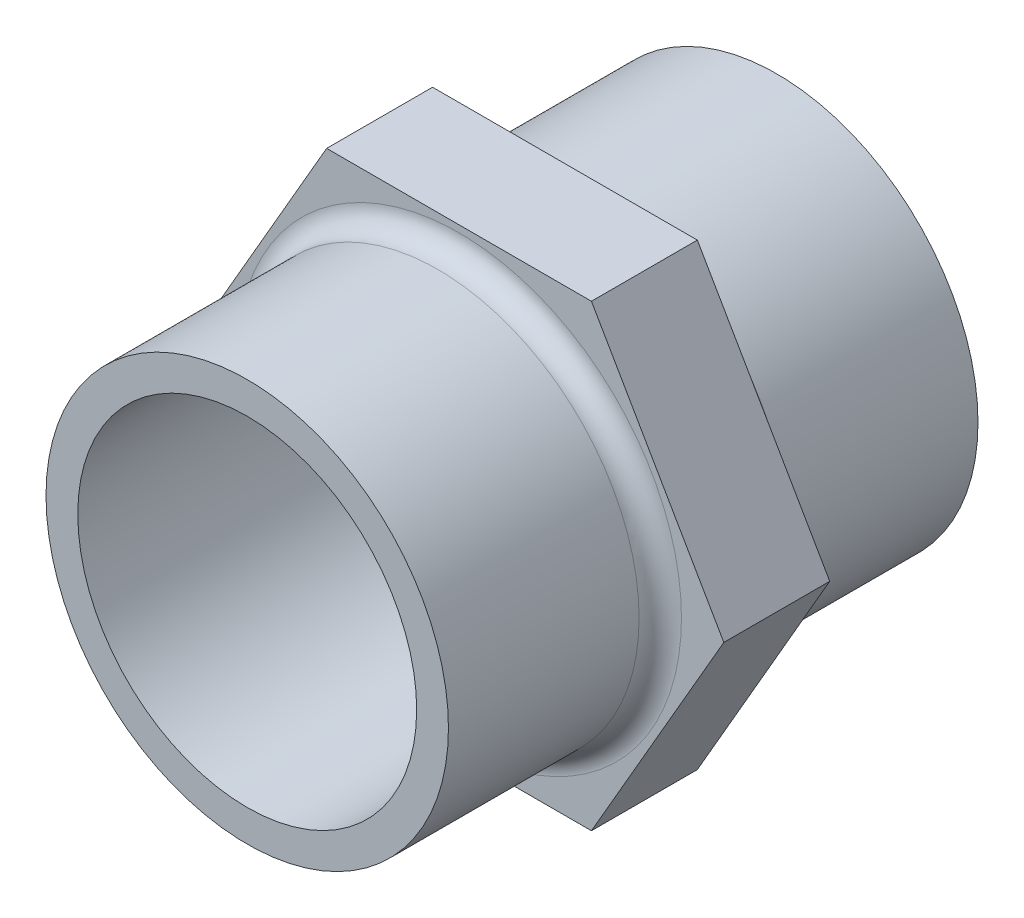
SolidWorks part; units mm, degrees
ref_plane "Ebene vorne" through (0, 0, 0) normal (0, 0, 1) x (1, 0, 0)
ref_plane "Ebene oben" through (0, 0, 0) normal (0, 1, 0) x (1, 0, 0)
ref_plane "Ebene rechts" through (0, 0, 0) normal (1, 0, 0) x (0, 0, -1)
sketch "Sketch1" plane through (0, 0, 0) normal (0, 0, 1) x (1, 0, 0)
  line L0 (-12.5, 0) -> (-6.25, 10.8253)
  line L1 (-6.25, 10.8253) -> (6.25, 10.8253)
  line L2 (6.25, 10.8253) -> (12.5, 0)
  line L3 (55, 0) -> (-55, 0) construction
  line L4 (-12.5, 0) -> (-6.25, -10.8253)
  line L5 (-6.25, -10.8253) -> (6.25, -10.8253)
  line L6 (6.25, -10.8253) -> (12.5, 0)
  circle A1 centre (0, 0) radius 12.5 construction
  dimension "D1" = 25
extrude "Boss-Extrude1" add sketch "Sketch1" along normal mid plane 5
sketch "Sketch2" plane through (0, 0, 0) normal (0, 0, 1) x (1, 0, 0)
  circle A0 centre (0, 0) radius 9.5
  dimension "D1" = 19
extrude "Boss-Extrude2" add sketch "Sketch2" along normal mid plane 25
sketch "Sketch3" plane through (0, 0, 0) normal (0, 0, 1) x (1, 0, 0)
  circle A0 centre (0, 0) radius 8
  dimension "D1" = 16
extrude "Cut-Extrude1" cut sketch "Sketch3" against normal through all both and the other way through all
fillet "Fillet1" radius 1 2 edges at (9.5, 0, -2.5) (9.5, 0, 2.5)
